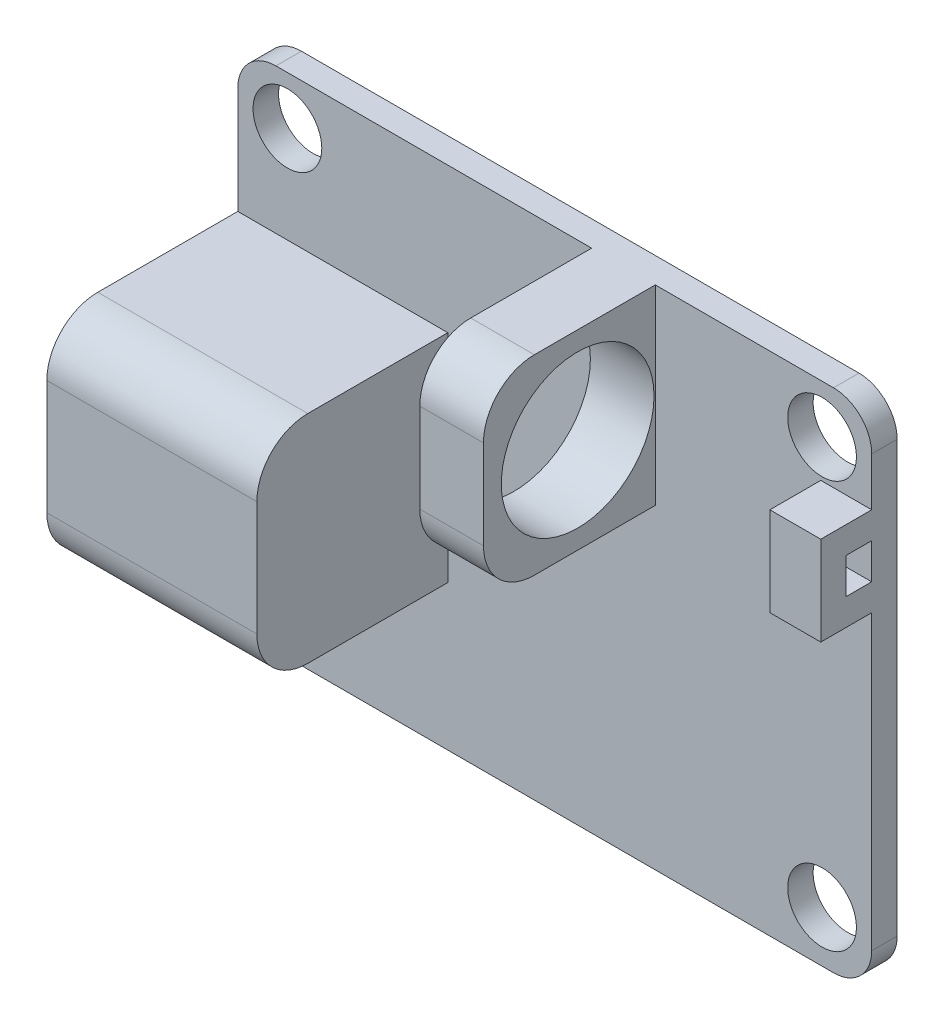
SolidWorks part; units mm, degrees
ref_plane "Alzado" through (0, 0, 0) normal (0, 0, 1) x (1, 0, 0)
ref_plane "Planta" through (0, 0, 0) normal (0, 1, 0) x (1, 0, 0)
ref_plane "Vista lateral" through (0, 0, 0) normal (1, 0, 0) x (0, 0, -1)
sketch "Croquis1" plane through (0, 0, 0) normal (0, 0, 1) x (1, 0, 0)
  line L1 (-56.8634, 16.1421) -> (-7.0634, 16.1421)
  line L2 (-56.8634, 16.1421) -> (-56.8634, -23.6579)
  line L3 (-56.8634, -23.6579) -> (-7.0634, -23.6579)
  line L4 (-7.0634, 16.1421) -> (-7.0634, -23.6579)
  circle A0 centre (-52.9634, 12.3421) radius 2.7
  circle A1 centre (-10.9634, 12.3421) radius 2.7
  circle A2 centre (-10.9634, -19.6579) radius 2.7
  circle A3 centre (-52.9634, -19.6579) radius 2.7
  dimension "D3" = 3.8
  dimension "D7" = 5.4
  dimension "D1" = 49.8
  dimension "D2" = 39.8
  dimension "D4" = 3.9
  dimension "D5" = 2
  dimension "D6" = 2
extrude "Saliente-Extruir1" add sketch "Croquis1" along normal blind 6
sketch "Croquis2" plane through (0, 0, 6) normal (0, 0, 1) x (1, 0, 0)
  line L0 (-56.8634, -23.6579) -> (-7.0634, 16.1421) construction
  line L2 (-49.9634, -16.7579) -> (-13.9634, -16.7579)
  line L3 (-51.9634, -14.7579) -> (-51.9634, 7.2421)
  line L4 (-49.9634, 9.2421) -> (-13.9634, 9.2421)
  line L5 (-11.9634, -14.7579) -> (-11.9634, 7.2421)
  line L6 (-51.9634, -16.7579) -> (-11.9634, 9.2421) construction
  line L7 (-51.9634, 9.2421) -> (-11.9634, -16.7579) construction
  arc A0 (-11.9634, 7.2421) -> (-13.9634, 9.2421) centre (-13.9634, 7.2421) ccw
  arc A1 (-11.9634, -14.7579) -> (-13.9634, -16.7579) centre (-13.9634, -14.7579) cw
  arc A2 (-49.9634, -16.7579) -> (-51.9634, -14.7579) centre (-49.9634, -14.7579) cw
  arc A3 (-49.9634, 9.2421) -> (-51.9634, 7.2421) centre (-49.9634, 7.2421) ccw
  point P4 (-31.9634, -3.7579)
  dimension "D3" = 2
  dimension "D1" = 40
  dimension "D2" = 26
extrude "Cortar-Extruir1" cut sketch "Croquis2" against normal blind 4
fillet "Redondeo1" radius 3 4 edges at (-56.8634, 16.1421, 3) (-7.0634, 16.1421, 3) (-7.0634, -23.6579, 3) (-56.8634, -23.6579, 3)
sketch "Croquis4" plane through (0, 0, 0) normal (0, 0, -1) x (-1, 0, 0)
  line L1 (56.8634, 13.1421) -> (56.8634, -20.6579) construction
  line L2 (56.8634, 4.2421) -> (61.8634, 4.2421)
  line L4 (61.8634, -11.7579) -> (56.8634, -11.7579)
  line L6 (56.8634, 4.2421) -> (61.8634, -11.7579) construction
  line L7 (57.8634, -0.2579) -> (61.8634, -0.2579)
  line L8 (57.8634, -7.2579) -> (61.8634, -7.2579)
  line L9 (61.8634, 4.2421) -> (61.8634, -0.2579)
  line L10 (61.8634, -7.2579) -> (61.8634, -11.7579)
  line L11 (56.8634, 4.2421) -> (56.8634, -0.4038)
  line L12 (56.8634, -7.112) -> (56.8634, -11.7579)
  arc A2 (57.8634, -0.2579) -> (56.8634, -0.4038) centre (57.8634, -3.7579) ccw
  arc A3 (57.8634, -7.2579) -> (56.8634, -7.112) centre (57.8634, -3.7579) cw
  dimension "D1" = 5
  dimension "D2" = 3.5
  dimension "D3" = 5
extrude "Saliente-Extruir3" add sketch "Croquis4" against normal blind 3
sketch "Croquis5" plane through (0, 0, 3) normal (0, 0, 1) x (1, 0, 0)
  circle A1 centre (-57.8634, -3.7579) radius 6.35
extrude "Cortar-Extruir2" cut sketch "Croquis5" along normal up to vertex (3 mm away)
sketch "Croquis6" plane through (0, 0, 3) normal (0, 0, 1) x (1, 0, 0)
  line L6 (-61.8634, 4.2421) -> (-51.9634, 4.2421)
  line L8 (-51.9634, -11.7579) -> (-61.8634, -11.7579)
  line L9 (-61.8634, 4.2421) -> (-61.8634, 1.1739)
  line L10 (-61.8634, -0.2579) -> (-61.8634, 4.2421) construction
  line L11 (-61.8634, -11.7579) -> (-61.8634, -8.6897)
  line L12 (-51.9634, 4.2421) -> (-48.9634, 4.2421)
  line L13 (-48.9634, 4.2421) -> (-48.9634, -11.7579)
  line L14 (-48.9634, -11.7579) -> (-51.9634, -11.7579)
  arc A5 (-61.8634, 1.1739) -> (-61.8634, -8.6897) centre (-57.8634, -3.7579) cw
extrude "Saliente-Extruir4" add sketch "Croquis6" along normal blind 10
sketch "Croquis7" plane through (0, 0, 2) normal (0, 0, 1) x (1, 0, 0)
  line L0 (-51.9634, -3.7579) -> (-51.9634, 4.2421)
  line L1 (-51.9634, 7.2421) -> (-51.9634, -14.7579) construction
  line L2 (-51.9634, 4.2421) -> (-48.9634, 4.2421)
  line L3 (-48.9634, 4.2421) -> (-48.9634, -11.7579)
  line L4 (-48.9634, -11.7579) -> (-51.9634, -11.7579)
  line L5 (-51.9634, -11.7579) -> (-51.9634, -3.7579)
extrude "Saliente-Extruir5" add sketch "Croquis7" along normal blind 2
sketch "Croquis8" plane through (0, 0, 3) normal (0, 0, 1) x (1, 0, 0)
  line L0 (-56.8634, -0.4038) -> (-56.8634, -7.112)
  arc A0 (-56.8634, -0.4038) -> (-56.8634, -7.112) centre (-56.8634, -3.7579) cw
extrude "Cortar-Extruir3" cut sketch "Croquis8" against normal up to vertex
sketch "Croquis9" plane through (0, 0, 6) normal (0, 0, 1) x (1, 0, 0)
  line L0 (-56.8634, -11.7579) -> (-56.8634, -27.4922)
  line L1 (-56.8634, -27.4922) -> (-1.8171, -27.4922)
  line L2 (-1.8171, -27.4922) -> (-1.8171, 22.8618)
  line L3 (-1.8171, 22.8618) -> (-56.8634, 22.8618)
  line L4 (-56.8634, 22.8618) -> (-56.8634, 4.2421)
  line L5 (-56.8634, 4.2421) -> (-47.1727, 4.2421)
  line L6 (-47.1727, 4.2421) -> (-47.1727, -11.7579)
  line L7 (-47.1727, -11.7579) -> (-56.8634, -11.7579)
extrude "Cortar-Extruir4" cut sketch "Croquis9" against normal blind 4
sketch "Croquis10" plane through (0, 0, 2) normal (0, 0, 1) x (1, 0, 0)
  line L0 (-7.0634, -20.6579) -> (-7.0634, 13.1421) construction
  line L1 (-7.0634, 9.3421) -> (-11.0634, 9.3421)
  line L2 (-7.0634, 9.3421) -> (-7.0634, 2.3421)
  line L3 (-7.0634, 2.3421) -> (-11.0634, 2.3421)
  line L4 (-11.0634, 9.3421) -> (-11.0634, 2.3421)
  circle A0 centre (-10.9634, 12.3421) radius 2.7 construction
  point P6 (-9.0634, 9.3421)
  dimension "D1" = 7
  dimension "D2" = 3
  dimension "D3" = 4
extrude "Saliente-Extruir6" add sketch "Croquis10" along normal blind 4
sketch "Croquis11" plane through (-7.0634, 0, 0) normal (1, 0, 0) x (0, 0, -1)
  line L0 (-6, 5.8421) -> (-2, 5.8421) construction
  line L1 (-6, 2.3421) -> (-6, 9.3421) construction
  line L2 (-2, 5.8421) -> (-2, 7.2421)
  line L3 (-2, 7.2421) -> (-4, 7.2421)
  line L4 (-4, 7.2421) -> (-4, 4.4421)
  line L5 (-4, 4.4421) -> (-2, 4.4421)
  line L6 (-2, 4.4421) -> (-2, 5.8421)
  dimension "D1" = 1.4
  dimension "D2" = 1.4
extrude "Cortar-Extruir5" cut sketch "Croquis11" against normal up to vertex
ref_plane "Plano2" through (-48.9634, 4.2421, 13) normal (0, 1, 0) x (1, 0, 0)
sketch "Croquis16" plane through (0, 0, 2) normal (0, 0, 1) x (1, 0, 0)
  line L1 (-64.1981, 16.945) -> (-35.2393, 16.945)
  line L2 (-64.1981, 16.945) -> (-64.1981, -30.9257)
  line L3 (-64.1981, -30.9257) -> (-35.2393, -30.9257)
  line L4 (-35.2393, 16.945) -> (-35.2393, -30.9257)
extrude "Cortar-Extruir6" cut sketch "Croquis16" along normal up to vertex (2 mm away)
sketch "Croquis17" plane through (0, 0, 2) normal (0, 0, 1) x (1, 0, 0)
  line L1 (-61.8634, 4.2421) -> (-56.8634, 4.2421)
  line L2 (-61.8634, 4.2421) -> (-61.8634, -11.7579)
  line L3 (-61.8634, -11.7579) -> (-56.8634, -11.7579)
  line L4 (-56.8634, 4.2421) -> (-56.8634, -11.7579)
extrude "Cortar-Extruir7" cut sketch "Croquis17" against normal blind 10
sketch "Croquis18" plane through (0, 0, 2) normal (0, 0, 1) x (1, 0, 0)
  line L0 (-56.8634, -0.4038) -> (-50.5134, -0.4038)
  line L1 (-56.8634, -7.112) -> (-50.5134, -7.112)
  line L2 (-56.8634, -0.4038) -> (-56.8634, -7.112)
  arc A0 (-50.5134, -0.4038) -> (-50.5134, -7.112) centre (-50.5134, -3.7579) cw
extrude "Cortar-Extruir8" cut sketch "Croquis18" against normal up to vertex (2 mm away)
sketch "Croquis19" plane through (0, 0, 2) normal (0, 0, 1) x (1, 0, 0)
  line L0 (-55.9053, -0.4038) -> (-56.8634, -0.4038)
  line L1 (-50.5134, -0.4038) -> (-56.8634, -0.4038) construction
  line L2 (-56.8634, -0.4038) -> (-56.8634, 2.5962)
  line L3 (-56.8634, 13.1421) -> (-56.8634, -0.4038) construction
  line L4 (-55.9053, -7.112) -> (-56.8634, -7.112)
  line L5 (-56.8634, -7.112) -> (-50.5134, -7.112) construction
  line L6 (-56.8634, -7.112) -> (-56.8634, -10.112)
  line L7 (-56.8634, -7.112) -> (-56.8634, -20.6579) construction
  circle A0 centre (-50.5134, -3.7579) radius 6.35
  arc A1 (-56.8634, 2.5962) -> (-56.8634, -10.112) centre (-50.5093, -3.7579) cw
  dimension "D1" = 3
sketch "Croquis20" plane through (0, 0, 2) normal (0, 0, 1) x (1, 0, 0)
  line L0 (-56.8634, -0.4038) -> (-56.8634, -7.112)
  line L1 (-56.8634, -7.112) -> (-50.5134, -7.112)
  line L2 (-56.8634, -0.4038) -> (-50.5134, -0.4038)
  arc A0 (-50.5134, -0.4038) -> (-50.5134, -7.112) centre (-50.5134, -3.7579) cw
extrude "Saliente-Extruir7" add sketch "Croquis20" against normal up to vertex (2 mm away)
sketch "Croquis22" plane through (-56.8634, 0, 0) normal (-1, 0, 0) x (0, 0, 1)
  line L0 (2, -3.7579) -> (2, 4.7421)
  line L1 (2, 13.1421) -> (2, -20.6579) construction
  line L2 (2, 4.7421) -> (13, 4.7421)
  line L3 (17, 0.7421) -> (17, -8.2579)
  line L4 (13, -12.2579) -> (2, -12.2579)
  line L5 (2, -12.2579) -> (2, -3.7579)
  line L6 (2, -3.7579) -> (8.55, -3.7579) construction
  arc A1 (17, -8.2579) -> (13, -12.2579) centre (13, -8.2579) cw
  arc A2 (13, 4.7421) -> (17, 0.7421) centre (13, 0.7421) cw
  circle A3 centre (8.55, -3.7579) radius 6.5
  dimension "D1" = 4
  dimension "D2" = 6.55
extrude "Saliente-Extruir9" add sketch "Croquis22" against normal blind 15
sketch "Croquis23" plane through (-41.8634, 0, 0) normal (1, 0, 0) x (0, 0, -1)
  line L0 (-13, -12.2579) -> (-2, -12.2579)
  line L1 (-2, -12.2579) -> (-2, 4.7421)
  line L2 (-2, 4.7421) -> (-13, 4.7421)
  line L3 (-17, 0.7421) -> (-17, -8.2579)
  arc A0 (-13, -12.2579) -> (-17, -8.2579) centre (-13, -8.2579) cw
  arc A1 (-17, 0.7421) -> (-13, 4.7421) centre (-13, 0.7421) cw
extrude "Saliente-Extruir10" add sketch "Croquis23" along normal blind 1.5
sketch "Croquis25" plane through (0, 0, 2) normal (0, 0, 1) x (1, 0, 0)
  line L1 (-29.0634, 16.1421) -> (-24.0634, 16.1421)
  line L2 (-29.0634, 16.1421) -> (-29.0634, 1.1421)
  line L3 (-29.0634, 1.1421) -> (-24.0634, 1.1421)
  line L4 (-24.0634, 16.1421) -> (-24.0634, 1.1421)
  line L6 (-7.0634, -20.6579) -> (-7.0634, 2.3421) construction
  dimension "D1" = 15
  dimension "D2" = 5
  dimension "D3" = 17
extrude "Saliente-Extruir11" add sketch "Croquis25" along normal blind 13.5
sketch "Croquis26" plane through (-24.0634, 0, 0) normal (1, 0, 0) x (0, 0, -1)
  line L0 (-2, 8.6421) -> (-8.1, 8.6421) construction
  line L1 (-2, 1.1421) -> (-2, 16.1421) construction
  circle A0 centre (-8.1, 8.6421) radius 6
extrude "Cortar-Extruir9" cut sketch "Croquis26" against normal up to vertex (5 mm away)
fillet "Redondeo2" radius 4 2 edges at (-26.5634, 1.1421, 15.5) (-26.5634, 16.1421, 15.5)
